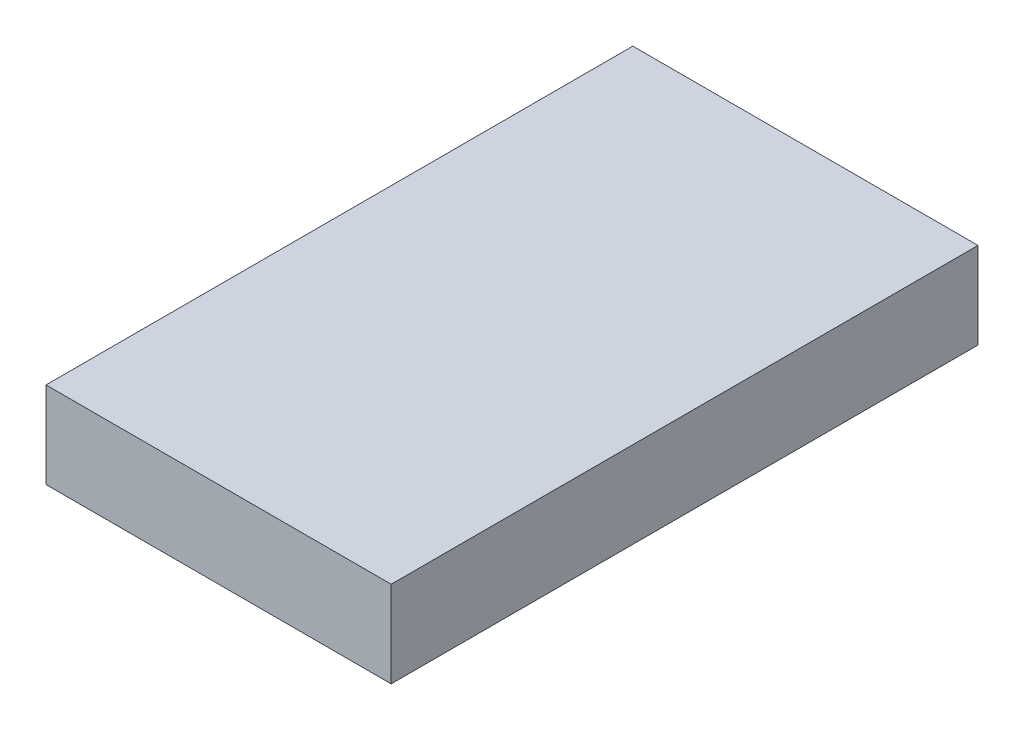
SolidWorks part; units mm, degrees
ref_plane "Front" through (0, 0, 0) normal (0, 0, 1) x (1, 0, 0)
ref_plane "Top" through (0, 0, 0) normal (0, 1, 0) x (1, 0, 0)
ref_plane "Right" through (0, 0, 0) normal (1, 0, 0) x (0, 0, -1)
sketch "Sketch1" plane through (0, 0, 0) normal (0, 1, 0) x (1, 0, 0)
  line L1 (-60, -102) -> (60, -102)
  line L2 (-60, -102) -> (-60, 102)
  line L3 (-60, 102) -> (60, 102)
  line L4 (60, -102) -> (60, 102)
  line L5 (-60, -102) -> (60, 102) construction
  line L6 (-60, 102) -> (60, -102) construction
  point P0 (0, 0)
  dimension "D1" = 204
  dimension "D2" = 120
extrude "Boss-Extrude1" add sketch "Sketch1" along normal blind 30
shell "Shell1" thickness 8
sketch "Sketch2" plane through (0, 0, 0) normal (0, -1, 0) x (1, 0, 0)
  line L0 (52, -94) -> (-52, -94) construction
  line L1 (52, 94) -> (52, -94) construction
  line L2 (-52, 94) -> (52, 94) construction
  line L3 (-52, -94) -> (-52, 94) construction
  line L4 (52, -94) -> (-52, -94)
  line L5 (52, 94) -> (52, -94)
  line L6 (-52, 94) -> (52, 94)
  line L7 (-52, -94) -> (-52, 94)
extrude "Cut-Extrude1" cut sketch "Sketch2" against normal blind 18
